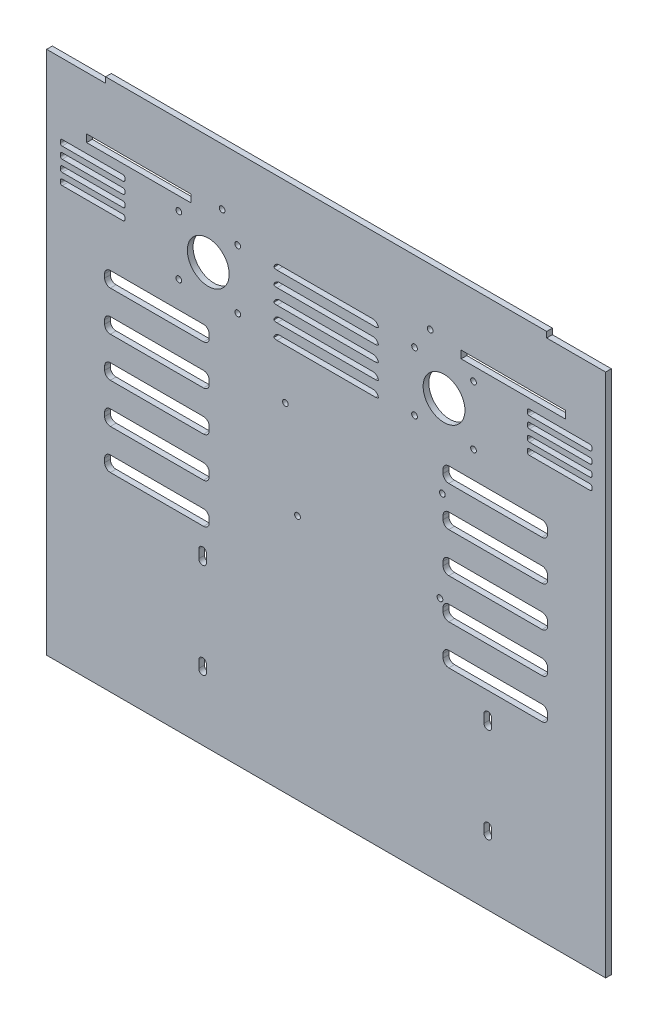
SolidWorks part; units mm, degrees
ref_plane "Front Plane" through (0, 0, 0) normal (0, 0, 1) x (1, 0, 0)
ref_plane "Top Plane" through (0, 0, 0) normal (0, 1, 0) x (1, 0, 0)
ref_plane "Right Plane" through (0, 0, 0) normal (1, 0, 0) x (0, 0, -1)
sketch "Sketch1" plane through (0, 0, 0) normal (0, 0, 1) x (1, 0, 0)
  line L0 (-46.5, 82.5) -> (-77.5, 82.5) construction
  line L1 (147, -123.5) -> (-147, -123.5)
  line L2 (147, -123.5) -> (147, 123.5)
  line L3 (147, 123.5) -> (-147, 123.5)
  line L4 (-147, -123.5) -> (-147, 123.5)
  line L5 (147, -123.5) -> (-147, 123.5) construction
  line L6 (147, 123.5) -> (-147, -123.5) construction
  line L7 (-46.5, 82.5) -> (-46.5, 113.5) construction
  line L8 (-46.5, 113.5) -> (-77.5, 113.5) construction
  line L9 (-77.5, 82.5) -> (-77.5, 113.5) construction
  line L10 (-46.5, 82.5) -> (-77.5, 113.5) construction
  line L11 (-46.5, 113.5) -> (-77.5, 82.5) construction
  line L12 (0, 123.5) -> (0, -133.2191) construction
  line L13 (46.5, 113.5) -> (77.5, 82.5) construction
  line L14 (46.5, 82.5) -> (77.5, 113.5) construction
  line L15 (77.5, 82.5) -> (77.5, 113.5) construction
  line L16 (46.5, 113.5) -> (77.5, 113.5) construction
  line L17 (46.5, 82.5) -> (46.5, 113.5) construction
  line L18 (46.5, 82.5) -> (77.5, 82.5) construction
  line L19 (-175.5662, 125.75) -> (218.0802, 125.75) construction
  line L20 (-147, 123.5) -> (147, 123.5)
  line L21 (-147, 123.5) -> (-147, 155.5)
  line L22 (-147, 155.5) -> (147, 155.5)
  line L23 (147, 123.5) -> (147, 155.5)
  line L24 (0, 155.5) -> (0, 123.5) construction
  line L25 (-147, 139.5) -> (147, 139.5) construction
  line L26 (147, 154) -> (116, 154) construction
  line L27 (-147, 155.5) -> (-116, 155.5)
  line L28 (-147, 155.5) -> (-147, 152.5)
  line L29 (-147, 152.5) -> (-116, 152.5)
  line L30 (-116, 155.5) -> (-116, 152.5)
  line L31 (-131.5, 152.5) -> (-131.5, 155.5) construction
  line L32 (-147, 154) -> (-116, 154) construction
  line L33 (131.5, 152.5) -> (131.5, 155.5) construction
  line L34 (116, 155.5) -> (116, 152.5)
  line L35 (147, 152.5) -> (116, 152.5)
  line L36 (147, 155.5) -> (147, 152.5)
  line L37 (147, 155.5) -> (116, 155.5)
  line L38 (-65, -39.5) -> (-65, -35.0783) construction
  line L39 (-67, -39.5) -> (-67, -35.0783)
  line L40 (-63, -39.5) -> (-63, -35.0783)
  line L41 (-65, -89.5) -> (-65, -85.5783) construction
  line L42 (-67, -89.5) -> (-67, -85.5783)
  line L43 (-63, -89.5) -> (-63, -85.5783)
  line L44 (85, -39.5) -> (85, -35.0783) construction
  line L45 (83, -39.5) -> (83, -35.0783)
  line L46 (87, -39.5) -> (87, -35.0783)
  line L47 (85, -89.5) -> (85, -85.5783) construction
  line L48 (83, -89.5) -> (83, -85.5783)
  line L49 (87, -89.5) -> (87, -85.5783)
  line L50 (-116.5, 64.5) -> (-61.5, 64.5) construction
  line L51 (113.5, 68.5) -> (64.5, 68.5)
  line L52 (116.5, 65.5) -> (116.5, 63.5)
  line L53 (113.5, 60.5) -> (64.5, 60.5)
  line L54 (61.5, 65.5) -> (61.5, 63.5)
  line L55 (89, 60.5) -> (89, 68.5) construction
  line L56 (116.5, 64.5) -> (61.5, 64.5) construction
  line L57 (-89, 60.5) -> (-89, 68.5) construction
  line L58 (-61.5, 65.5) -> (-61.5, 63.5)
  line L59 (-113.5, 60.5) -> (-64.5, 60.5)
  line L60 (-116.5, 65.5) -> (-116.5, 63.5)
  line L61 (-113.5, 68.5) -> (-64.5, 68.5)
  line L62 (113.5, 47.5) -> (64.5, 47.5)
  line L63 (116.5, 44.5) -> (116.5, 42.5)
  line L64 (113.5, 39.5) -> (64.5, 39.5)
  line L65 (61.5, 44.5) -> (61.5, 42.5)
  line L66 (-61.5, 44.5) -> (-61.5, 42.5)
  line L67 (-113.5, 39.5) -> (-64.5, 39.5)
  line L68 (-116.5, 44.5) -> (-116.5, 42.5)
  line L69 (-113.5, 47.5) -> (-64.5, 47.5)
  line L70 (-116.5, 43.5) -> (-61.5, 43.5) construction
  line L71 (89, 39.5) -> (89, 47.5) construction
  line L72 (116.5, 43.5) -> (61.5, 43.5) construction
  line L73 (-89, 39.5) -> (-89, 47.5) construction
  line L74 (113.5, 26.5) -> (64.5, 26.5)
  line L75 (116.5, 23.5) -> (116.5, 21.5)
  line L76 (113.5, 18.5) -> (64.5, 18.5)
  line L77 (61.5, 23.5) -> (61.5, 21.5)
  line L78 (-61.5, 23.5) -> (-61.5, 21.5)
  line L79 (-113.5, 18.5) -> (-64.5, 18.5)
  line L80 (-116.5, 23.5) -> (-116.5, 21.5)
  line L81 (-113.5, 26.5) -> (-64.5, 26.5)
  line L82 (-116.5, 22.5) -> (-61.5, 22.5) construction
  line L83 (89, 18.5) -> (89, 26.5) construction
  line L84 (116.5, 22.5) -> (61.5, 22.5) construction
  line L85 (-89, 18.5) -> (-89, 26.5) construction
  line L86 (113.5, 5.5) -> (64.5, 5.5)
  line L87 (116.5, 2.5) -> (116.5, 0.5)
  line L88 (113.5, -2.5) -> (64.5, -2.5)
  line L89 (61.5, 2.5) -> (61.5, 0.5)
  line L90 (-61.5, 2.5) -> (-61.5, 0.5)
  line L91 (-113.5, -2.5) -> (-64.5, -2.5)
  line L92 (-116.5, 2.5) -> (-116.5, 0.5)
  line L93 (-113.5, 5.5) -> (-64.5, 5.5)
  line L94 (-116.5, 1.5) -> (-61.5, 1.5) construction
  line L95 (89, -2.5) -> (89, 5.5) construction
  line L96 (116.5, 1.5) -> (61.5, 1.5) construction
  line L97 (-89, -2.5) -> (-89, 5.5) construction
  line L98 (113.5, -15.5) -> (64.5, -15.5)
  line L99 (116.5, -18.5) -> (116.5, -20.5)
  line L100 (113.5, -23.5) -> (64.5, -23.5)
  line L101 (61.5, -18.5) -> (61.5, -20.5)
  line L102 (-61.5, -18.5) -> (-61.5, -20.5)
  line L103 (-113.5, -23.5) -> (-64.5, -23.5)
  line L104 (-116.5, -18.5) -> (-116.5, -20.5)
  line L105 (-113.5, -15.5) -> (-64.5, -15.5)
  line L106 (-116.5, -19.5) -> (-61.5, -19.5) construction
  line L107 (89, -23.5) -> (89, -15.5) construction
  line L108 (116.5, -19.5) -> (61.5, -19.5) construction
  line L109 (-89, -23.5) -> (-89, -15.5) construction
  line L110 (-24.542, 107.5) -> (24.542, 107.5)
  line L111 (-24.542, 115.5) -> (24.542, 115.5)
  line L112 (-25.8417, 104.5) -> (25.8417, 104.5)
  line L113 (-25.8417, 112.5) -> (25.8417, 112.5)
  line L114 (0, 104.5) -> (0, 107.5) construction
  line L115 (0, 112.5) -> (0, 115.5) construction
  line L116 (-27.5, 113) -> (27.5, 113) construction
  line L117 (-27.5, 105) -> (27.5, 105) construction
  line L118 (-24.542, 99.5) -> (24.542, 99.5)
  line L119 (-25.8417, 96.5) -> (25.8417, 96.5)
  line L120 (0, 96.5) -> (0, 99.5) construction
  line L121 (-27.5, 97) -> (27.5, 97) construction
  line L122 (-24.542, 91.5) -> (24.542, 91.5)
  line L123 (-25.8417, 88.5) -> (25.8417, 88.5)
  line L124 (0, 88.5) -> (0, 91.5) construction
  line L125 (-27.5, 89) -> (27.5, 89) construction
  line L126 (-24.542, 83.5) -> (24.542, 83.5)
  line L127 (-25.8417, 80.5) -> (25.8417, 80.5)
  line L128 (0, 80.5) -> (0, 83.5) construction
  line L129 (-27.5, 81) -> (27.5, 81) construction
  line L130 (-159.7263, 124.5) -> (156.3882, 124.5) construction
  line L131 (126, 122.5) -> (71, 122.5) construction
  line L132 (-126, 124.5) -> (-71, 124.5)
  line L133 (-126, 124.5) -> (-126, 120.5)
  line L134 (-126, 120.5) -> (-71, 120.5)
  line L135 (-71, 124.5) -> (-71, 120.5)
  line L136 (-98.5, 120.5) -> (-98.5, 124.5) construction
  line L137 (-126, 122.5) -> (-71, 122.5) construction
  line L138 (98.5, 120.5) -> (98.5, 124.5) construction
  line L139 (71, 124.5) -> (71, 120.5)
  line L140 (126, 120.5) -> (71, 120.5)
  line L141 (126, 124.5) -> (126, 120.5)
  line L142 (126, 124.5) -> (71, 124.5)
  line L143 (57.643, 132.7279) -> (57.643, 166.0775) construction
  line L144 (138.8255, 115.5) -> (106.8255, 115.5)
  line L145 (139.8255, 114.5) -> (139.8255, 113.5)
  line L146 (138.8255, 112.5) -> (106.8255, 112.5)
  line L147 (105.8255, 114.5) -> (105.8255, 113.5)
  line L148 (122.8255, 112.5) -> (122.8255, 115.5) construction
  line L149 (139.8255, 114) -> (105.8255, 114) construction
  line L150 (138.8255, 109.5) -> (106.8255, 109.5)
  line L151 (139.8255, 108.5) -> (139.8255, 107.5)
  line L152 (138.8255, 106.5) -> (106.8255, 106.5)
  line L153 (105.8255, 108.5) -> (105.8255, 107.5)
  line L154 (122.8255, 106.5) -> (122.8255, 109.5) construction
  line L155 (139.8255, 108) -> (105.8255, 108) construction
  line L156 (138.8255, 103.5) -> (106.8255, 103.5)
  line L157 (139.8255, 102.5) -> (139.8255, 101.5)
  line L158 (138.8255, 100.5) -> (106.8255, 100.5)
  line L159 (105.8255, 102.5) -> (105.8255, 101.5)
  line L160 (122.8255, 100.5) -> (122.8255, 103.5) construction
  line L161 (139.8255, 102) -> (105.8255, 102) construction
  line L162 (138.8255, 97.5) -> (106.8255, 97.5)
  line L163 (139.8255, 96.5) -> (139.8255, 95.5)
  line L164 (138.8255, 94.5) -> (106.8255, 94.5)
  line L165 (105.8255, 96.5) -> (105.8255, 95.5)
  line L166 (122.8255, 94.5) -> (122.8255, 97.5) construction
  line L167 (139.8255, 96) -> (105.8255, 96) construction
  line L168 (-139.8255, 96) -> (-105.8255, 96) construction
  line L169 (-122.8255, 94.5) -> (-122.8255, 97.5) construction
  line L170 (-139.8255, 102) -> (-105.8255, 102) construction
  line L171 (-122.8255, 100.5) -> (-122.8255, 103.5) construction
  line L172 (-139.8255, 108) -> (-105.8255, 108) construction
  line L173 (-122.8255, 106.5) -> (-122.8255, 109.5) construction
  line L174 (-139.8255, 114) -> (-105.8255, 114) construction
  line L175 (-122.8255, 112.5) -> (-122.8255, 115.5) construction
  line L176 (-105.8255, 96.5) -> (-105.8255, 95.5)
  line L177 (-138.8255, 94.5) -> (-106.8255, 94.5)
  line L178 (-139.8255, 96.5) -> (-139.8255, 95.5)
  line L179 (-138.8255, 97.5) -> (-106.8255, 97.5)
  line L180 (-105.8255, 102.5) -> (-105.8255, 101.5)
  line L181 (-138.8255, 100.5) -> (-106.8255, 100.5)
  line L182 (-139.8255, 102.5) -> (-139.8255, 101.5)
  line L183 (-138.8255, 103.5) -> (-106.8255, 103.5)
  line L184 (-105.8255, 108.5) -> (-105.8255, 107.5)
  line L185 (-138.8255, 106.5) -> (-106.8255, 106.5)
  line L186 (-139.8255, 108.5) -> (-139.8255, 107.5)
  line L187 (-138.8255, 109.5) -> (-106.8255, 109.5)
  line L188 (-105.8255, 114.5) -> (-105.8255, 113.5)
  line L189 (-138.8255, 112.5) -> (-106.8255, 112.5)
  line L190 (-139.8255, 114.5) -> (-139.8255, 113.5)
  line L191 (-138.8255, 115.5) -> (-106.8255, 115.5)
  circle A0 centre (-77.5, 113.5) radius 1.5
  circle A1 centre (-46.5, 113.5) radius 1.5
  circle A2 centre (77.5, 82.5) radius 1.5
  circle A3 centre (-62, 98) radius 11
  circle A4 centre (-46.5, 82.5) radius 1.5
  circle A5 centre (-77.5, 82.5) radius 1.5
  circle A6 centre (46.5, 82.5) radius 1.5
  circle A7 centre (62, 98) radius 11
  circle A8 centre (46.5, 113.5) radius 1.5
  circle A9 centre (77.5, 113.5) radius 1.5
  circle A10 centre (85, -39.5) radius 2 construction
  circle A11 centre (85, -89.5) radius 2 construction
  circle A12 centre (-65, -39.5) radius 2 construction
  circle A13 centre (-65, -89.5) radius 2 construction
  circle A14 centre (61.1213, 54.1951) radius 1.5
  circle A15 centre (-54.7, 125.75) radius 1.5
  circle A16 centre (-15.0787, 5.9351) radius 1.5
  circle A17 centre (59.8513, 5.9351) radius 1.5
  circle A18 centre (-21.4287, 54.1951) radius 1.5
  circle A19 centre (54.7, 125.75) radius 1.5
  arc A20 (-67, -39.5) -> (-63, -39.5) centre (-65, -39.5) ccw
  arc A21 (-63, -35.0783) -> (-67, -35.0783) centre (-65, -35.0783) ccw
  arc A22 (83, -39.5) -> (87, -39.5) centre (85, -39.5) ccw
  arc A23 (-67, -89.5) -> (-63, -89.5) centre (-65, -89.5) ccw
  arc A24 (-63, -85.5783) -> (-67, -85.5783) centre (-65, -85.5783) ccw
  arc A25 (87, -35.0783) -> (83, -35.0783) centre (85, -35.0783) ccw
  arc A26 (83, -89.5) -> (87, -89.5) centre (85, -89.5) ccw
  arc A27 (87, -85.5783) -> (83, -85.5783) centre (85, -85.5783) ccw
  arc A28 (64.5, 68.5) -> (61.5, 65.5) centre (64.5, 65.5) ccw
  arc A29 (64.5, 60.5) -> (61.5, 63.5) centre (64.5, 63.5) cw
  arc A30 (116.5, 63.5) -> (113.5, 60.5) centre (113.5, 63.5) cw
  arc A31 (113.5, 68.5) -> (116.5, 65.5) centre (113.5, 65.5) cw
  arc A32 (-113.5, 68.5) -> (-116.5, 65.5) centre (-113.5, 65.5) ccw
  arc A33 (-116.5, 63.5) -> (-113.5, 60.5) centre (-113.5, 63.5) ccw
  arc A34 (-64.5, 60.5) -> (-61.5, 63.5) centre (-64.5, 63.5) ccw
  arc A35 (-64.5, 68.5) -> (-61.5, 65.5) centre (-64.5, 65.5) cw
  arc A36 (64.5, 47.5) -> (61.5, 44.5) centre (64.5, 44.5) ccw
  arc A37 (64.5, 39.5) -> (61.5, 42.5) centre (64.5, 42.5) cw
  arc A38 (116.5, 42.5) -> (113.5, 39.5) centre (113.5, 42.5) cw
  arc A39 (113.5, 47.5) -> (116.5, 44.5) centre (113.5, 44.5) cw
  arc A40 (-113.5, 47.5) -> (-116.5, 44.5) centre (-113.5, 44.5) ccw
  arc A41 (-116.5, 42.5) -> (-113.5, 39.5) centre (-113.5, 42.5) ccw
  arc A42 (-64.5, 39.5) -> (-61.5, 42.5) centre (-64.5, 42.5) ccw
  arc A43 (-64.5, 47.5) -> (-61.5, 44.5) centre (-64.5, 44.5) cw
  arc A44 (64.5, 26.5) -> (61.5, 23.5) centre (64.5, 23.5) ccw
  arc A45 (64.5, 18.5) -> (61.5, 21.5) centre (64.5, 21.5) cw
  arc A46 (116.5, 21.5) -> (113.5, 18.5) centre (113.5, 21.5) cw
  arc A47 (113.5, 26.5) -> (116.5, 23.5) centre (113.5, 23.5) cw
  arc A48 (-113.5, 26.5) -> (-116.5, 23.5) centre (-113.5, 23.5) ccw
  arc A49 (-116.5, 21.5) -> (-113.5, 18.5) centre (-113.5, 21.5) ccw
  arc A50 (-64.5, 18.5) -> (-61.5, 21.5) centre (-64.5, 21.5) ccw
  arc A51 (-64.5, 26.5) -> (-61.5, 23.5) centre (-64.5, 23.5) cw
  arc A52 (64.5, 5.5) -> (61.5, 2.5) centre (64.5, 2.5) ccw
  arc A53 (64.5, -2.5) -> (61.5, 0.5) centre (64.5, 0.5) cw
  arc A54 (116.5, 0.5) -> (113.5, -2.5) centre (113.5, 0.5) cw
  arc A55 (113.5, 5.5) -> (116.5, 2.5) centre (113.5, 2.5) cw
  arc A56 (-113.5, 5.5) -> (-116.5, 2.5) centre (-113.5, 2.5) ccw
  arc A57 (-116.5, 0.5) -> (-113.5, -2.5) centre (-113.5, 0.5) ccw
  arc A58 (-64.5, -2.5) -> (-61.5, 0.5) centre (-64.5, 0.5) ccw
  arc A59 (-64.5, 5.5) -> (-61.5, 2.5) centre (-64.5, 2.5) cw
  arc A60 (64.5, -15.5) -> (61.5, -18.5) centre (64.5, -18.5) ccw
  arc A61 (64.5, -23.5) -> (61.5, -20.5) centre (64.5, -20.5) cw
  arc A62 (116.5, -20.5) -> (113.5, -23.5) centre (113.5, -20.5) cw
  arc A63 (113.5, -15.5) -> (116.5, -18.5) centre (113.5, -18.5) cw
  arc A64 (-113.5, -15.5) -> (-116.5, -18.5) centre (-113.5, -18.5) ccw
  arc A65 (-116.5, -20.5) -> (-113.5, -23.5) centre (-113.5, -20.5) ccw
  arc A66 (-64.5, -23.5) -> (-61.5, -20.5) centre (-64.5, -20.5) ccw
  arc A67 (-64.5, -15.5) -> (-61.5, -18.5) centre (-64.5, -18.5) cw
  arc A68 (25.8417, 112.5) -> (27.5, 113) centre (25.8417, 115.5) ccw
  arc A69 (-27.5, 113) -> (-25.8417, 112.5) centre (-25.8417, 115.5) ccw
  arc A70 (-24.542, 115.5) -> (-27.5, 113) centre (-24.542, 112.5) ccw
  arc A71 (24.542, 115.5) -> (27.5, 113) centre (24.542, 112.5) cw
  arc A72 (25.8417, 104.5) -> (27.5, 105) centre (25.8417, 107.5) ccw
  arc A73 (-27.5, 105) -> (-25.8417, 104.5) centre (-25.8417, 107.5) ccw
  arc A74 (-24.542, 107.5) -> (-27.5, 105) centre (-24.542, 104.5) ccw
  arc A75 (24.542, 107.5) -> (27.5, 105) centre (24.542, 104.5) cw
  arc A76 (25.8417, 96.5) -> (27.5, 97) centre (25.8417, 99.5) ccw
  arc A77 (-27.5, 97) -> (-25.8417, 96.5) centre (-25.8417, 99.5) ccw
  arc A78 (-24.542, 99.5) -> (-27.5, 97) centre (-24.542, 96.5) ccw
  arc A79 (24.542, 99.5) -> (27.5, 97) centre (24.542, 96.5) cw
  arc A80 (25.8417, 88.5) -> (27.5, 89) centre (25.8417, 91.5) ccw
  arc A81 (-27.5, 89) -> (-25.8417, 88.5) centre (-25.8417, 91.5) ccw
  arc A82 (-24.542, 91.5) -> (-27.5, 89) centre (-24.542, 88.5) ccw
  arc A83 (24.542, 91.5) -> (27.5, 89) centre (24.542, 88.5) cw
  arc A84 (25.8417, 80.5) -> (27.5, 81) centre (25.8417, 83.5) ccw
  arc A85 (-27.5, 81) -> (-25.8417, 80.5) centre (-25.8417, 83.5) ccw
  arc A86 (-24.542, 83.5) -> (-27.5, 81) centre (-24.542, 80.5) ccw
  arc A87 (24.542, 83.5) -> (27.5, 81) centre (24.542, 80.5) cw
  arc A88 (106.8255, 115.5) -> (105.8255, 114.5) centre (106.8255, 114.5) ccw
  arc A89 (106.8255, 112.5) -> (105.8255, 113.5) centre (106.8255, 113.5) cw
  arc A90 (139.8255, 113.5) -> (138.8255, 112.5) centre (138.8255, 113.5) cw
  arc A91 (138.8255, 115.5) -> (139.8255, 114.5) centre (138.8255, 114.5) cw
  arc A92 (106.8255, 109.5) -> (105.8255, 108.5) centre (106.8255, 108.5) ccw
  arc A93 (106.8255, 106.5) -> (105.8255, 107.5) centre (106.8255, 107.5) cw
  arc A94 (139.8255, 107.5) -> (138.8255, 106.5) centre (138.8255, 107.5) cw
  arc A95 (138.8255, 109.5) -> (139.8255, 108.5) centre (138.8255, 108.5) cw
  arc A96 (106.8255, 103.5) -> (105.8255, 102.5) centre (106.8255, 102.5) ccw
  arc A97 (106.8255, 100.5) -> (105.8255, 101.5) centre (106.8255, 101.5) cw
  arc A98 (139.8255, 101.5) -> (138.8255, 100.5) centre (138.8255, 101.5) cw
  arc A99 (138.8255, 103.5) -> (139.8255, 102.5) centre (138.8255, 102.5) cw
  arc A100 (106.8255, 97.5) -> (105.8255, 96.5) centre (106.8255, 96.5) ccw
  arc A101 (106.8255, 94.5) -> (105.8255, 95.5) centre (106.8255, 95.5) cw
  arc A102 (139.8255, 95.5) -> (138.8255, 94.5) centre (138.8255, 95.5) cw
  arc A103 (138.8255, 97.5) -> (139.8255, 96.5) centre (138.8255, 96.5) cw
  arc A104 (-138.8255, 97.5) -> (-139.8255, 96.5) centre (-138.8255, 96.5) ccw
  arc A105 (-139.8255, 95.5) -> (-138.8255, 94.5) centre (-138.8255, 95.5) ccw
  arc A106 (-106.8255, 94.5) -> (-105.8255, 95.5) centre (-106.8255, 95.5) ccw
  arc A107 (-106.8255, 97.5) -> (-105.8255, 96.5) centre (-106.8255, 96.5) cw
  arc A108 (-138.8255, 103.5) -> (-139.8255, 102.5) centre (-138.8255, 102.5) ccw
  arc A109 (-139.8255, 101.5) -> (-138.8255, 100.5) centre (-138.8255, 101.5) ccw
  arc A110 (-106.8255, 100.5) -> (-105.8255, 101.5) centre (-106.8255, 101.5) ccw
  arc A111 (-106.8255, 103.5) -> (-105.8255, 102.5) centre (-106.8255, 102.5) cw
  arc A112 (-138.8255, 109.5) -> (-139.8255, 108.5) centre (-138.8255, 108.5) ccw
  arc A113 (-139.8255, 107.5) -> (-138.8255, 106.5) centre (-138.8255, 107.5) ccw
  arc A114 (-106.8255, 106.5) -> (-105.8255, 107.5) centre (-106.8255, 107.5) ccw
  arc A115 (-106.8255, 109.5) -> (-105.8255, 108.5) centre (-106.8255, 108.5) cw
  arc A116 (-138.8255, 115.5) -> (-139.8255, 114.5) centre (-138.8255, 114.5) ccw
  arc A117 (-139.8255, 113.5) -> (-138.8255, 112.5) centre (-138.8255, 113.5) ccw
  arc A118 (-106.8255, 112.5) -> (-105.8255, 113.5) centre (-106.8255, 113.5) ccw
  arc A119 (-106.8255, 115.5) -> (-105.8255, 114.5) centre (-106.8255, 114.5) cw
  point P0 (0, 0)
  point P63 (131.5, 154)
  point P65 (-65, -37.2892)
  point P73 (-65, -87.5392)
  point P79 (85, -37.2892)
  point P86 (85, -87.5392)
  point P119 (-89, 64.5)
  point P132 (-131.5, 154)
  point P154 (-89, 43.5)
  point P159 (89, 43.5)
  point P164 (89, 64.5)
  point P193 (-89, 22.5)
  point P198 (89, 22.5)
  point P227 (-89, 1.5)
  point P232 (89, 1.5)
  point P261 (-89, -19.5)
  point P266 (89, -19.5)
  point P274 (0, 139.5)
  point P293 (0, 105)
  point P306 (0, 97)
  point P319 (0, 89)
  point P332 (0, 81)
  point P345 (98.5, 122.5)
  point P364 (122.8255, 114)
  point P381 (0, 113)
  point P384 (122.8255, 108)
  point P401 (122.8255, 102)
  point P418 (122.8255, 96)
  point P483 (-122.8255, 96)
  point P484 (-122.8255, 102)
  point P485 (-122.8255, 108)
  point P486 (-122.8255, 114)
  point P552 (-98.5, 122.5)
  dimension "D3" = 22
  dimension "D5" = 3
  dimension "D6" = 85
  dimension "D8" = 3
  dimension "D9" = 3
  dimension "D10" = 3
  dimension "D11" = 2
  dimension "D12" = 2
  dimension "D13" = 2
  dimension "D14" = 2
  dimension "D19" = 3
  dimension "D20" = 3
  dimension "D21" = 3
  dimension "D22" = 3
  dimension "D31" = 3
  dimension "D35" = 2
  dimension "D38" = 3
  dimension "D44" = 3
  dimension "D52" = 1
  dimension "D1" = 294
  dimension "D2" = 247
  dimension "D4" = 31
  dimension "D7" = 10
  dimension "D15" = 82
  dimension "D16" = 150
  dimension "D17" = 50
  dimension "D18" = 34
  dimension "D23" = 82.55
  dimension "D24" = 48.26
  dimension "D25" = 74.93
  dimension "D26" = 48.26
  dimension "D27" = 69.3049
  dimension "D28" = 85.8787
  dimension "D29" = 124.5
  dimension "D30" = 2.25
  dimension "D32" = 54.7
  dimension "D33" = 31
  dimension "D34" = 3
  dimension "D36" = 55
  dimension "D37" = 8
  dimension "D39" = 89
  dimension "D40" = 55
  dimension "D42" = 55
  dimension "D43" = 3
  dimension "D45" = 8
  dimension "D47" = 32
  dimension "D48" = 4
  dimension "D49" = 55
  dimension "D50" = 21
  dimension "D51" = 34
  dimension "D53" = 3
  dimension "D54" = 34
  dimension "D55" = 34
  dimension "D56" = 34
  dimension "D57" = 3
  dimension "D58" = 3
  dimension "D59" = 3
  dimension "D60" = 3
  dimension "D61" = 3
  dimension "D62" = 3
  dimension "D63" = 5
  dimension "D41" = 5
  dimension "D46" = 5
extrude "Boss-Extrude1" add sketch "Sketch1" along normal blind 3 contours L4 L1 L2 L3 A18 A17 A16 A14 A13 A12 A11 A10 A8 A6 A5 A4 A3 A0 A1 A2 A7 A9 | L3 L23 L22 L21
